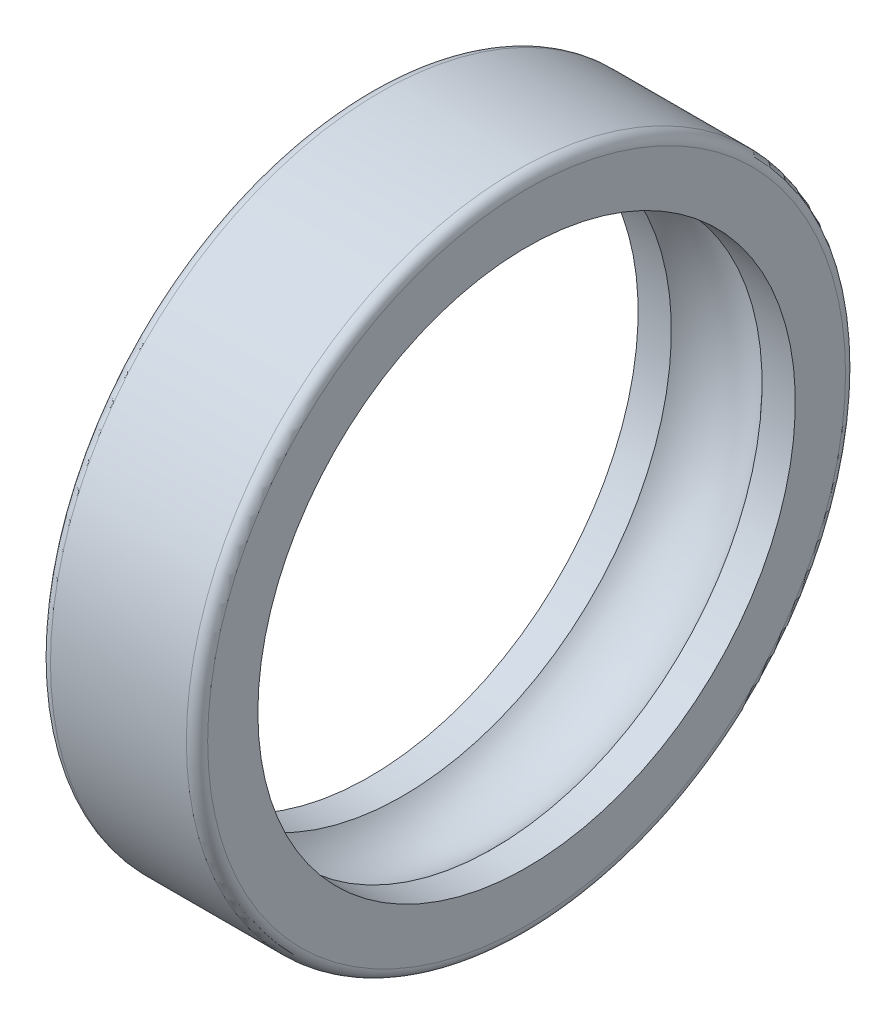
SolidWorks part; units mm, degrees
ref_plane "Front Plane" through (0, 0, 0) normal (0, 0, 1) x (1, 0, 0)
ref_plane "Top Plane" through (0, 0, 0) normal (0, 1, 0) x (1, 0, 0)
ref_plane "Right Plane" through (0, 0, 0) normal (1, 0, 0) x (0, 0, -1)
sketch "Sketch2" plane through (0, 0, 0) normal (0, 0, 1) x (1, 0, 0)
  line L0 (-15.5, 0) -> (36.3776, 0) construction
  line L1 (0, 0) -> (0, 53) construction
  line L2 (15.5, 65) -> (-15.5, 65)
  line L3 (15.5, 65) -> (15.5, 53)
  line L4 (15.5, 53) -> (8.9443, 53)
  line L5 (-15.5, 65) -> (-15.5, 53)
  line L6 (15.5, 65) -> (-15.5, 53) construction
  line L7 (15.5, 53) -> (-15.5, 65) construction
  line L8 (-8.9443, 53) -> (-15.5, 53)
  arc A0 (-8.9443, 53) -> (8.9443, 53) centre (0, 45) cw
  point P3 (0, 59)
  dimension "D4" = 8
  dimension "D5" = 12
  dimension "D1" = 31
  dimension "D2" = 53
  dimension "D3" = 65
revolve "Revolve1" add sketch "Sketch2" angle 360 about L0
fillet "Fillet1" radius 2.1 2 edges at (15.5, 0, 65) (-15.5, 0, 65)
